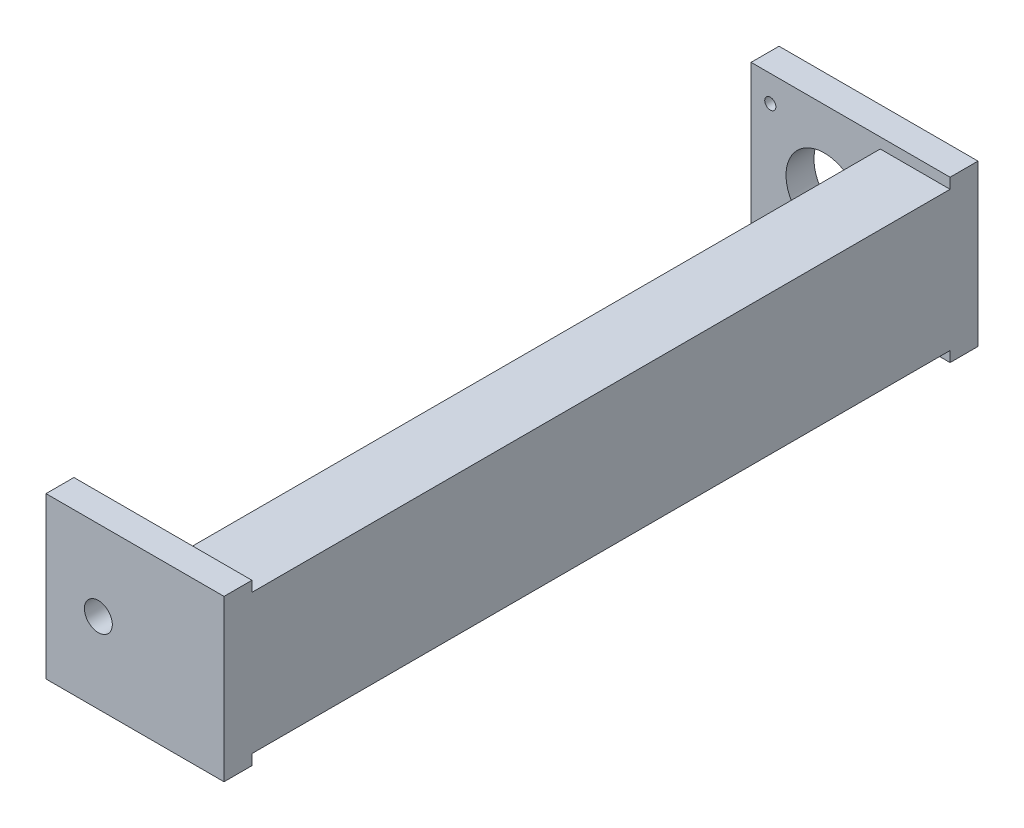
SolidWorks part; units mm, degrees
ref_plane "前视基准面" through (0, 0, 0) normal (0, 0, 1) x (1, 0, 0)
ref_plane "上视基准面" through (0, 0, 0) normal (0, 1, 0) x (1, 0, 0)
ref_plane "右视基准面" through (0, 0, 0) normal (1, 0, 0) x (0, 0, -1)
sketch "草图1" plane through (0, 0, 0) normal (0, 0, 1) x (1, 0, 0)
  line L1 (-28.5, -23) -> (28.5, -23)
  line L2 (-28.5, -23) -> (-28.5, 23)
  line L3 (-28.5, 23) -> (28.5, 23)
  line L4 (28.5, -23) -> (28.5, 23)
  line L5 (-28.5, -23) -> (28.5, 23) construction
  line L6 (-28.5, 23) -> (28.5, -23) construction
  line L7 (-23, -15.5) -> (8, -15.5) construction
  line L8 (-23, -15.5) -> (-23, 15.5) construction
  line L9 (-23, 15.5) -> (8, 15.5) construction
  line L10 (8, -15.5) -> (8, 15.5) construction
  line L11 (-23, -15.5) -> (8, 15.5) construction
  line L12 (-23, 15.5) -> (8, -15.5) construction
  circle A0 centre (-7.5, 0) radius 11
  circle A1 centre (-23, 15.5) radius 1.6
  circle A2 centre (8, 15.5) radius 1.6
  circle A3 centre (8, -15.5) radius 1.6
  circle A4 centre (-23, -15.5) radius 1.6
  point P0 (0, 0)
  dimension "D3" = 22
  dimension "D5" = 3.2
  dimension "D6" = 3.2
  dimension "D7" = 3.2
  dimension "D8" = 3.2
  dimension "D1" = 57
  dimension "D2" = 46
  dimension "D4" = 21
  dimension "D9" = 31
  dimension "D10" = 31
extrude "凸台-拉伸1" add sketch "草图1" along normal blind 8
sketch "草图2" plane through (0, 0, 8) normal (0, 0, 1) x (1, 0, 0)
  line L0 (28.5, -23) -> (28.5, 23) construction
  line L1 (28.5, 20) -> (8.5, 20)
  line L2 (28.5, 20) -> (28.5, -20)
  line L3 (28.5, -20) -> (8.5, -20)
  line L4 (8.5, 20) -> (8.5, -20)
  point P6 (8.5, 0)
  dimension "D1" = 20
  dimension "D2" = 40
extrude "凸台-拉伸2" add sketch "草图2" along normal blind 200
sketch "草图3" plane through (0, 0, 208) normal (0, 0, 1) x (1, 0, 0)
  line L0 (28.5, -20) -> (28.5, 20) construction
  line L5 (28.5, 23) -> (-22.5, 23)
  line L6 (28.5, 23) -> (28.5, -23)
  line L7 (28.5, -23) -> (-22.5, -23)
  line L8 (-22.5, 23) -> (-22.5, -23)
  circle A0 centre (-7.5, 0) radius 4
  point P0 (0, 0)
  point P8 (28.5, 0)
  dimension "D3" = 8
  dimension "D1" = 46
  dimension "D2" = 51
  dimension "D4" = 15
extrude "凸台-拉伸3" add sketch "草图3" along normal blind 8
